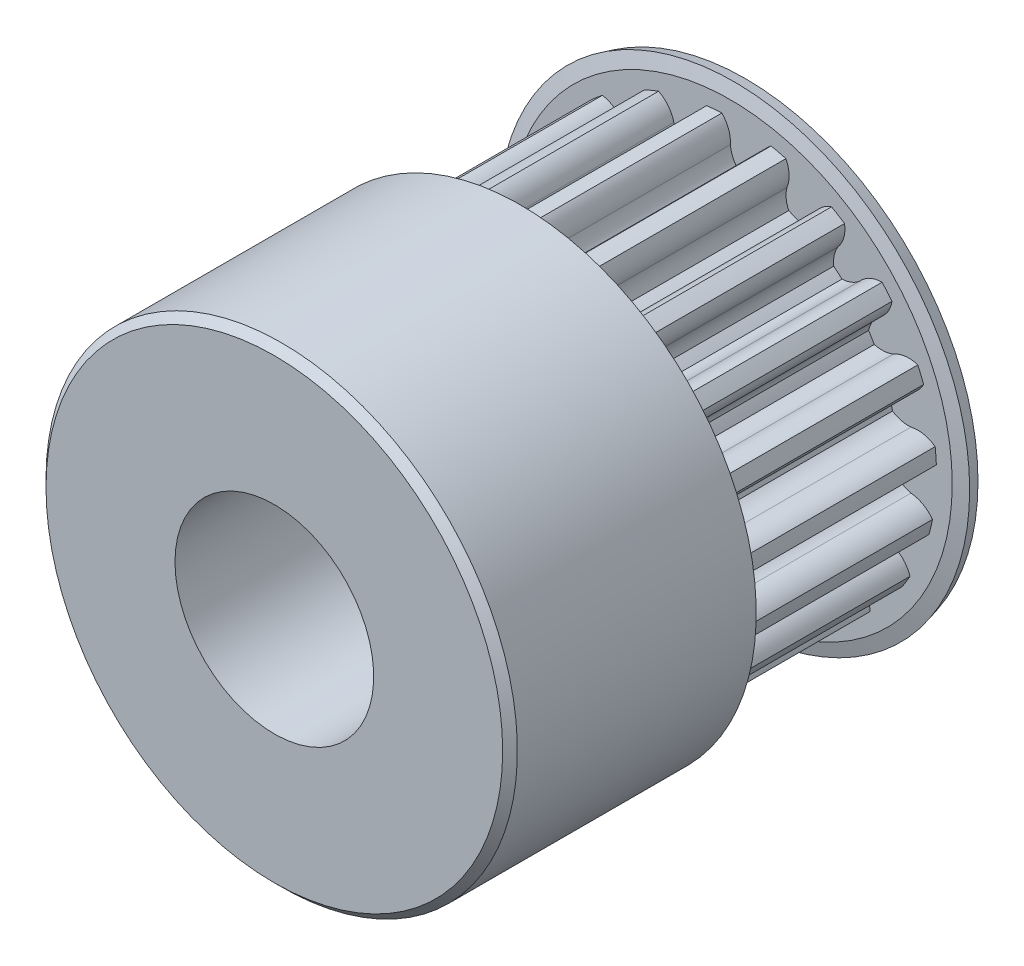
SolidWorks part; units mm, degrees
ref_plane "Front Plane" through (0, 0, 0) normal (0, 0, 1) x (1, 0, 0)
ref_plane "Top Plane" through (0, 0, 0) normal (0, 1, 0) x (1, 0, 0)
ref_plane "Right Plane" through (0, 0, 0) normal (1, 0, 0) x (0, 0, -1)
sketch "Sketch1" plane through (0, 0, 0) normal (0, 0, 1) x (1, 0, 0)
  circle A0 centre (0, 0) radius 7
  dimension "D1" = 14
extrude "Boss-Extrude1" add sketch "Sketch1" along normal blind 7
sketch "Sketch2" plane through (0, 0, 7) normal (0, 0, 1) x (1, 0, 0)
  circle A0 centre (0, 0) radius 6.365
  circle A1 centre (0, 0) radius 5.62
  circle A2 centre (0, 6.365) radius 1
  circle A3 centre (-0.9969, 6.2864) radius 1
  circle A4 centre (0.9969, 6.2864) radius 1
  circle A5 centre (1.9692, 6.0527) radius 1
  circle M1 centre (0, 0) radius 7
  dimension "D1" = 12.73
  dimension "D2" = 11.24
extrude "Cut-Extrude1" cut sketch "Sketch2" against normal blind 7 contours A5 A2 M1 | A4 A0 A2 M1 | A4 A3 M1 | A5 A0 A3 A4 A1 A2
pattern_circular "CirPattern1" count 20 over 360 about axis through (0, 0, 0) along (0, 0, 1) of "Cut-Extrude1"
sketch "Sketch3" plane through (0, 0, 7) normal (0, 0, 1) x (1, 0, 0)
  circle A0 centre (0, 0) radius 2.5
extrude "Cut-Extrude2" cut sketch "Sketch3" against normal blind 7
sketch "Sketch4" plane through (0, 0, 0) normal (1, 0, 0) x (0, 0, -1)
  line L0 (0, 0) -> (0, 8) construction
  line L1 (0, 0) -> (0, -8) construction
  line L2 (0, -6.994) -> (0.4, -6.994) construction
  line L3 (0, 0) -> (0, -2.4987) construction
  line L4 (0, -7.5328) -> (0.1252, -8)
  line L5 (0.1252, -8) -> (0.5116, -7.8965)
  line L6 (0.5116, -7.8965) -> (0.4, -7.4801)
  line L7 (0, -2.4987) -> (0, -7.5328)
  line L8 (0, -2.4987) -> (0.4, -2.4987)
  line L9 (0.4, -2.4987) -> (0.4, -7.4801)
  line L10 (0, 0) -> (2.2534, 0) construction
  dimension "D1" = 15
revolve "Revolve3" add sketch "Sketch4" angle 360 about L10
sketch "Sketch7" plane through (0, 0, 0) normal (1, 0, 0) x (0, 0, -1)
  line L0 (0, 0) -> (-7, -0.0031) construction
  line L1 (-7, -0.0031) -> (-7, 3.3706) construction
  line L2 (-7, 3.6489) -> (-7, 3.0923) construction
  line L3 (-7, 3.3706) -> (-7, 7.5328)
  line L4 (0.1252, 8) -> (-7, 8) construction
  line L5 (0, 7.5328) -> (-7, 7.5328) construction
  line L6 (-7, 7.5328) -> (-7.1252, 8)
  line L7 (-7, 8) -> (-7.1252, 8) construction
  line L8 (-7.1252, 8) -> (-15.2352, 8)
  line L9 (-7, 3.3706) -> (-15.4852, 3.3706)
  line L10 (-15.4852, 3.3706) -> (-15.4852, 7.75)
  line L11 (-15.2352, 8) -> (-15.4852, 7.75)
  line L12 (-7, -0.0031) -> (-8.9131, -0.0031) construction
  point P15 (-15.4852, 8)
  dimension "D1" = 15
revolve "Revolve4" add sketch "Sketch7" angle 360 about L12
